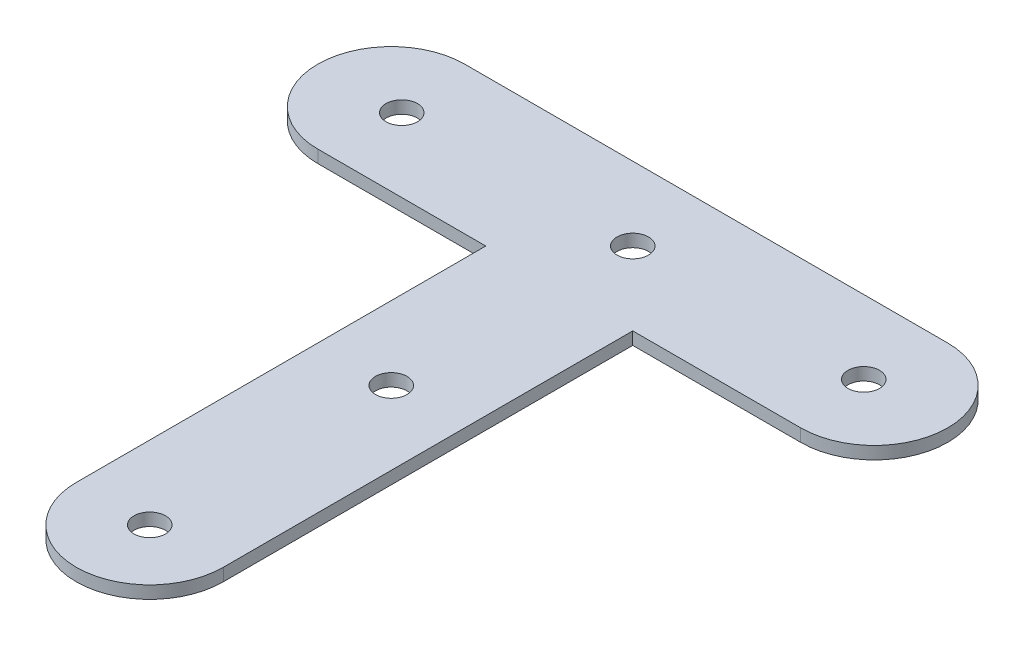
SolidWorks part; units mm, degrees
material "201 退火不锈钢 (SS)"
ref_plane "前视基准面" through (0, 0, 0) normal (0, 0, 1) x (1, 0, 0)
ref_plane "上视基准面" through (0, 0, 0) normal (0, 1, 0) x (1, 0, 0)
ref_plane "右视基准面" through (0, 0, 0) normal (1, 0, 0) x (0, 0, -1)
sketch "草图1" plane through (0, 0, 0) normal (0, 1, 0) x (1, 0, 0)
  line L0 (-22, 0) -> (22, 0) construction
  line L1 (0, 0) -> (0, -46) construction
  line L2 (-23, 7) -> (23, 7)
  line L4 (23, -7) -> (7, -7)
  line L5 (7, -7) -> (7, -46)
  line L7 (-7, -46) -> (-7, -7)
  line L8 (-7, -7) -> (-23, -7)
  circle A0 centre (22, 0) radius 1.5
  circle A1 centre (-22, 0) radius 1.5
  circle A2 centre (0, 0) radius 1.5
  circle A3 centre (0, -23) radius 1.5
  circle A4 centre (0, -46) radius 1.5
  arc A5 (7, -46) -> (-7, -46) centre (0, -46) cw
  arc A6 (23, -7) -> (23, 7) centre (23, 0) ccw
  arc A7 (-23, -7) -> (-23, 7) centre (-23, 0) cw
  point P22 (30, 0)
  point P23 (-30, 0)
  point P24 (0, -53)
  dimension "D7" = 3
  dimension "D1" = 46
  dimension "D2" = 44
  dimension "D3" = 14
  dimension "D4" = 14
  dimension "D5" = 60
  dimension "D6" = 60
extrude "凸台-拉伸1" add sketch "草图1" along normal blind 1.2
